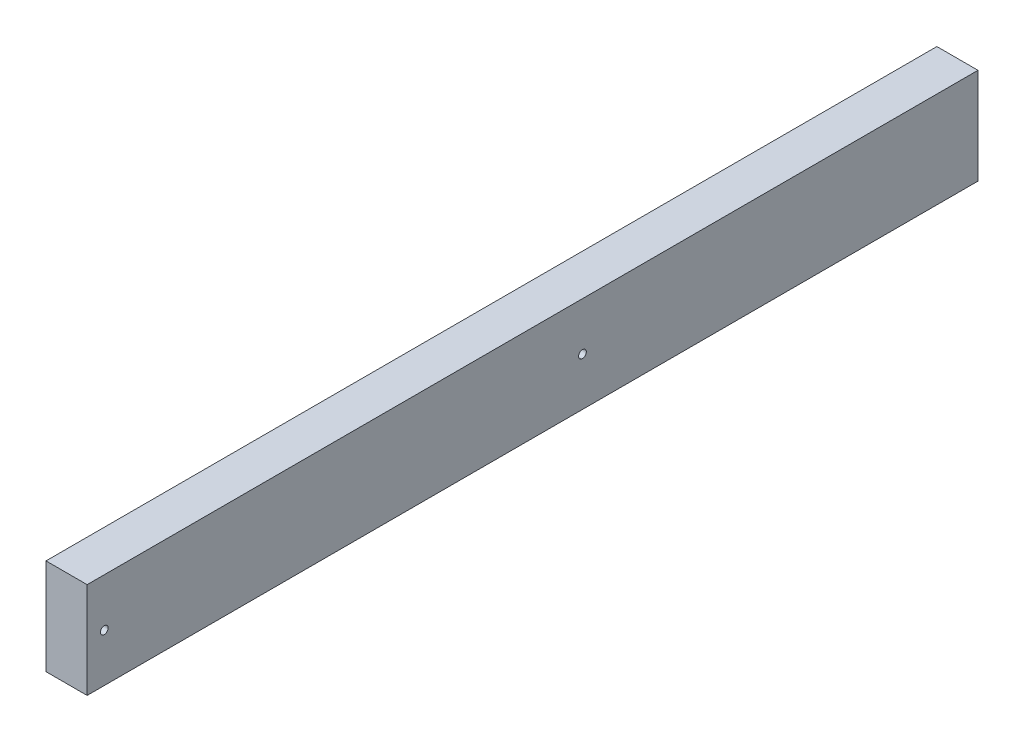
SolidWorks part; units mm, degrees
material "Pine"
ref_plane "Front Plane" through (0, 0, 0) normal (0, 0, 1) x (1, 0, 0)
ref_plane "Top Plane" through (0, 0, 0) normal (0, 1, 0) x (1, 0, 0)
ref_plane "Right Plane" through (0, 0, 0) normal (1, 0, 0) x (0, 0, -1)
sketch "Sketch1" plane through (0, 0, 0) normal (1, 0, 0) x (0, 0, -1)
  line L1 (0, 88.9) -> (825.1772, 88.9)
  line L4 (0, 88.9) -> (0, 0)
  line L5 (825.1772, 88.9) -> (825.1772, 0)
  line L7 (825.1772, 0) -> (0, 0)
  dimension "D1" = 88.9
  dimension "D2" = 90
  dimension "D3" = 90
  dimension "D4" = 90
  dimension "D5" = 825.1772
extrude "Boss-Extrude1" add sketch "Sketch1" along normal blind 38.1
sketch "Sketch2" plane through (38.1, 0, 0) normal (1, 0, 0) x (0, 0, -1)
  line L0 (0, 88.9) -> (0, 0) construction
  line L1 (0, 0) -> (825.1772, 0) construction
  circle A0 centre (15.875, 44.45) radius 3.5719
  circle A1 centre (458.7875, 44.45) radius 3.5719
  dimension "D2" = 7.1437
  dimension "D6" = 7.1437
  dimension "D1" = 15.875
  dimension "D3" = 44.45
  dimension "D4" = 458.7875
  dimension "D5" = 44.45
extrude "Cut-Extrude1" cut sketch "Sketch2" against normal through all
